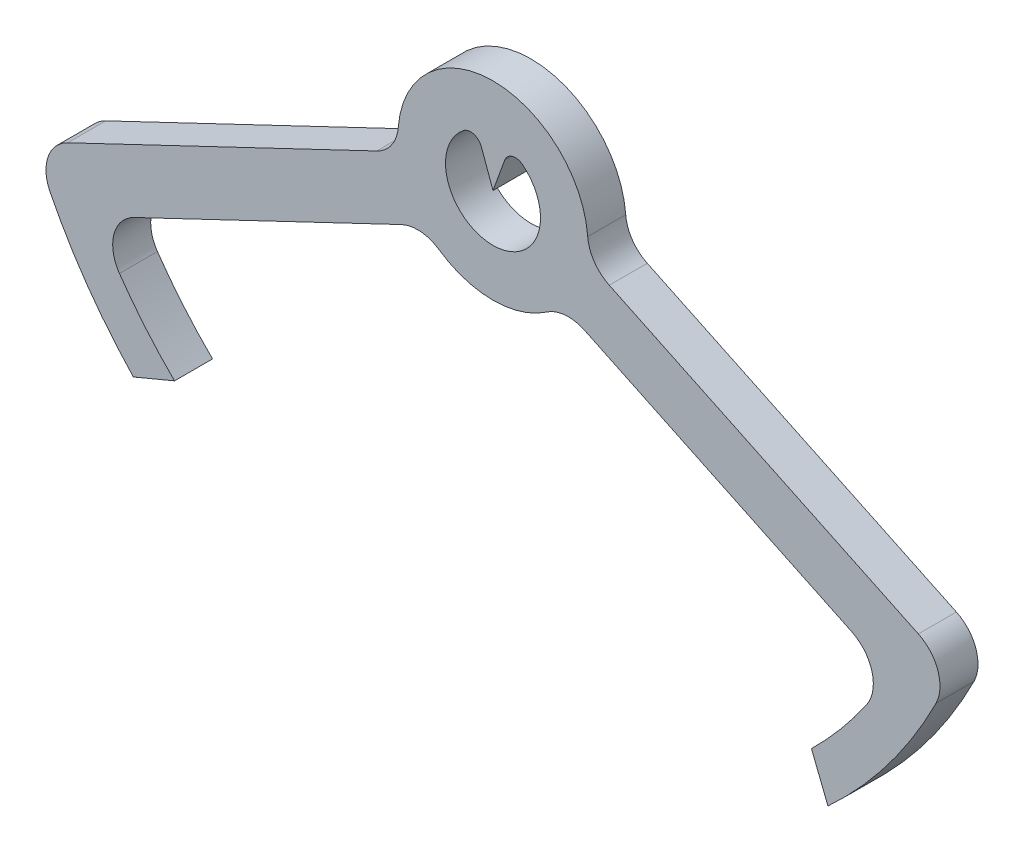
SolidWorks part; units mm, degrees
ref_plane "Front Plane" through (0, 0, 0) normal (0, 0, 1) x (1, 0, 0)
ref_plane "Top Plane" through (0, 0, 0) normal (0, 1, 0) x (1, 0, 0)
ref_plane "Right Plane" through (0, 0, 0) normal (1, 0, 0) x (0, 0, -1)
sketch "Sketch1" plane through (0, 0, 0) normal (0, 0, 1) x (1, 0, 0)
  line L0 (17.8779, -42.7612) -> (-94.6262, -89.7976) construction
  line L1 (43.0668, 17.1286) -> (88.1318, -96.1796) construction
  line L2 (-83.792, -85.268) -> (-94.6262, -89.7976)
  line L3 (83.792, -85.268) -> (88.1318, -96.1796)
  line L4 (-117.7439, -56.1614) -> (0, 0) construction
  line L5 (0, 0) -> (117.7439, -56.1614) construction
  line L6 (-104.4607, -58.1351) -> (-18.2964, -17.0365)
  line L7 (-120.778, -49.2992) -> (-24.7541, -3.4977)
  line L8 (24.7541, -3.4977) -> (120.778, -49.2992)
  line L9 (18.2964, -17.0365) -> (104.4607, -58.1351)
  line L10 (0, 0) -> (0, 119.548) construction
  line L11 (-83.792, -85.268) -> (0, 0) construction
  line L12 (-4.2753, 11.7462) -> (0, 0)
  line L13 (0, 0) -> (4.2753, 11.7462)
  circle A0 centre (0, 0) radius 46.348 construction
  circle A1 centre (0, 0) radius 130.452 construction
  circle A2 centre (0, 0) radius 119.548 construction
  arc A3 (-83.792, -85.268) -> (-104.4607, -58.1351) centre (0, 0) cw
  arc A4 (-94.6262, -89.7976) -> (-120.778, -49.2992) centre (0, 0) cw
  arc A5 (83.792, -85.268) -> (104.4607, -58.1351) centre (0, 0) ccw
  arc A6 (88.1318, -96.1796) -> (120.778, -49.2992) centre (0, 0) ccw
  circle A7 centre (0, 0) radius 25
  circle A8 centre (0, 0) radius 12.5
  point P9 (-83.792, -85.268)
  point P10 (83.792, -85.268)
  point P27 (6.25, 10.8253)
  dimension "impulse base circle" = 92.696
  dimension "external arc" = 260.904
  dimension "internal arc" = 239.096
  dimension "D6" = 25
  dimension "D7" = 50
  dimension "pallet opening" = 167.584
  dimension "arm thickness" = 15
  dimension "D1" = 15
  dimension "D2" = 7.5
  dimension "D3" = 7.5
  dimension "D4" = 115.5
  dimension "D5" = 115.5
  dimension "clearance angle" = 20
  dimension "D8" = 20
  dimension "D9" = 20
extrude "Boss-Extrude1" add sketch "Sketch1" along normal blind 10 contours A7 L7 A4 L2 A3 L6 | A7 A8 | A7 L9 A5 L3 A6 L8 | L13 A8 L12
fillet "Fillet1" radius 10 4 edges at (-18.2964, -17.0365, 5) (18.2964, -17.0365, 5) (24.7541, -3.4977, 5) (-24.7541, -3.4977, 5)
fillet "Fillet2" radius 10 4 edges at (120.778, -49.2992, 5) (104.4607, -58.1351, 5) (-104.4607, -58.1351, 5) (-120.778, -49.2992, 5)
fillet "Fillet3" radius 3 2 edges at (4.2753, 11.7462, 5) (-4.2753, 11.7462, 5)
equation "\"D1@Sketch1\"=\"arm thickness@Sketch1\""
equation "\"D2@Sketch1\"=\"arm thickness@Sketch1\"*0.5"
equation "\"D3@Sketch1\"=\"arm thickness@Sketch1\"*0.5"
equation "\"D5@Sketch1\"=\"D4@Sketch1\""
equation "\"D9@Sketch1\"=\"D8@Sketch1\""
